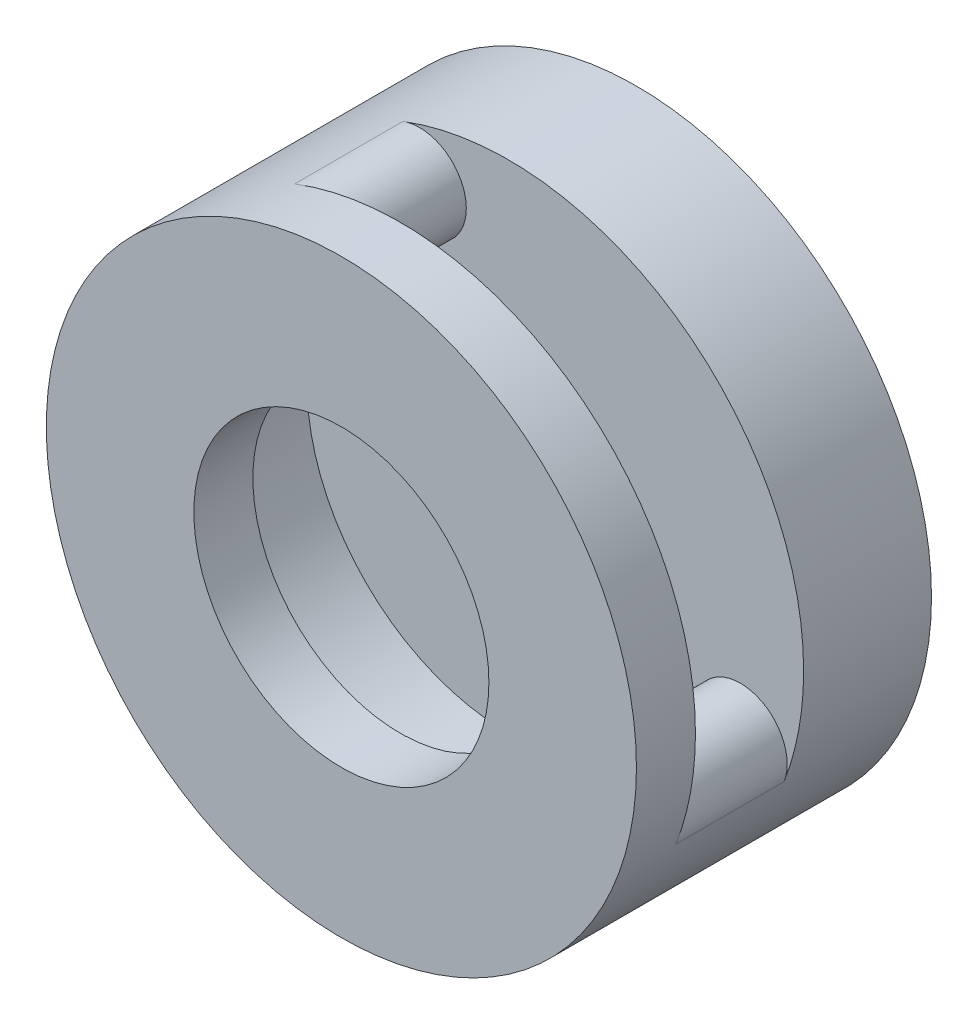
SolidWorks part; units mm, degrees
ref_plane "前视基准面" through (0, 0, 0) normal (0, 0, 1) x (1, 0, 0)
ref_plane "上视基准面" through (0, 0, 0) normal (0, 1, 0) x (1, 0, 0)
ref_plane "右视基准面" through (0, 0, 0) normal (1, 0, 0) x (0, 0, -1)
sketch "草图1" plane through (0, 0, 0) normal (0, 0, 1) x (1, 0, 0)
  circle A0 centre (0, 0) radius 3
  dimension "D1" = 6
extrude "凸台-拉伸1" add sketch "草图1" along normal blind 3
sketch "草图2" plane through (0, 0, 3) normal (0, 0, 1) x (1, 0, 0)
  circle A0 centre (0, 0) radius 1.5
  dimension "D1" = 3
extrude "切除-拉伸1" cut sketch "草图2" against normal blind 0.6
sketch "草图3" plane through (0, 0, 2.4) normal (0, 0, 1) x (1, 0, 0)
  line L0 (0, 0) -> (2.8225, 2.8225) construction
  line L1 (0, 0) -> (1.2811, 0) construction
  line L2 (-0.9049, 2.3573) -> (0, 0) construction
  line L3 (-1.0751, 2.8007) -> (-1.3439, 3.5009)
  line L4 (2.8007, -1.0751) -> (3.5009, -1.3439)
  arc A0 (-0.7347, 1.9138) -> (1.9138, -0.7347) centre (0, 0) ccw
  arc A1 (-0.7347, 1.9138) -> (-1.0751, 2.8007) centre (-0.9049, 2.3573) ccw
  arc A5 (1.9138, -0.7347) -> (2.8007, -1.0751) centre (2.3573, -0.9049) cw
  circle A6 centre (0, 0) radius 3
  circle A7 centre (0, 0) radius 3 construction
  arc A8 (3.5009, -1.3439) -> (-1.3439, 3.5009) centre (0, 0) ccw
  dimension "D1" = 4.1
  dimension "D3" = 0
  dimension "D5" = 7.5
  dimension "D2" = 45
  dimension "D4" = 66
extrude "切除-拉伸2" cut sketch "草图3" against normal blind 1.1
